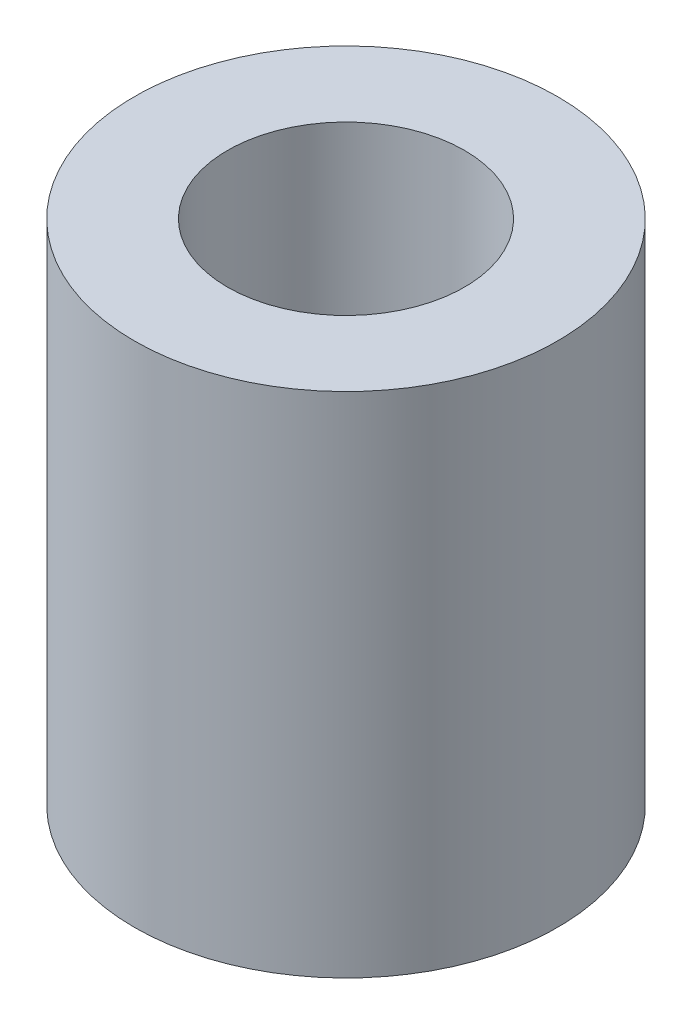
SolidWorks part; units mm, degrees
ref_plane "前视基准面" through (0, 0, 0) normal (0, 0, 1) x (1, 0, 0)
ref_plane "上视基准面" through (0, 0, 0) normal (0, 1, 0) x (1, 0, 0)
ref_plane "右视基准面" through (0, 0, 0) normal (1, 0, 0) x (0, 0, -1)
sketch "草图1" plane through (0, 0, 0) normal (0, 1, 0) x (1, 0, 0)
  circle A0 centre (0, 0) radius 12.5
extrude "凸台-拉伸1" add sketch "草图1" along normal blind 30
sketch "草图2" plane through (0, 30, 0) normal (0, 1, 0) x (1, 0, 0)
  circle A0 centre (0, 0) radius 7
extrude "切除-拉伸1" cut sketch "草图2" against normal blind 10
sketch "草图3" plane through (0, 0, 0) normal (0, -1, 0) x (1, 0, 0)
  circle A0 centre (0, 0) radius 4
extrude "切除-拉伸2" cut sketch "草图3" against normal blind 10
